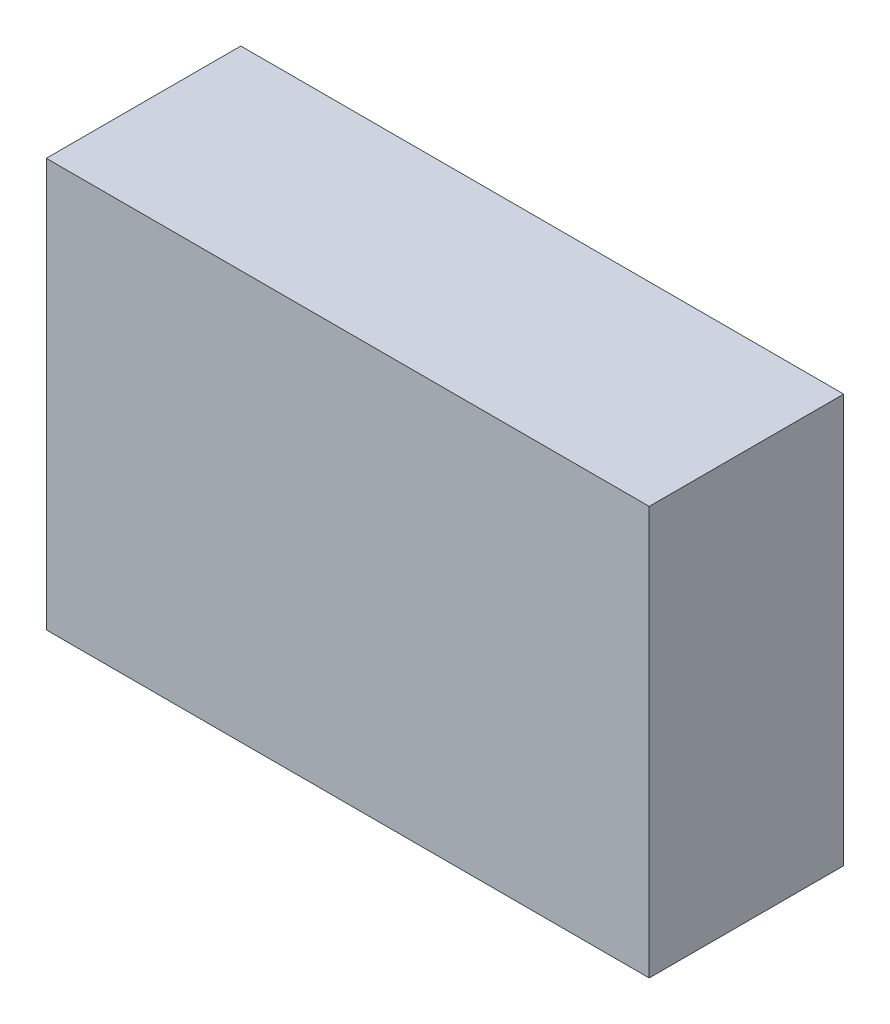
SolidWorks part; units mm, degrees
ref_plane "Front Plane" through (0, 0, 0) normal (0, 0, 1) x (1, 0, 0)
ref_plane "Top Plane" through (0, 0, 0) normal (0, 1, 0) x (1, 0, 0)
ref_plane "Right Plane" through (0, 0, 0) normal (1, 0, 0) x (0, 0, -1)
sketch "Sketch1" plane through (0, 0, 0) normal (0, 0, 1) x (1, 0, 0)
  line L1 (-31, -21) -> (31, -21)
  line L2 (-31, -21) -> (-31, 21)
  line L3 (-31, 21) -> (31, 21)
  line L4 (31, -21) -> (31, 21)
  line L5 (-31, -21) -> (31, 21) construction
  line L6 (-31, 21) -> (31, -21) construction
  line L8 (-31, -21) -> (-31, 21) construction
  line L9 (31, -21) -> (-31, -21) construction
  point P4 (0, 0)
  point P5 (0, 0)
extrude "Boss-Extrude1" add sketch "Sketch1" along normal blind 20
